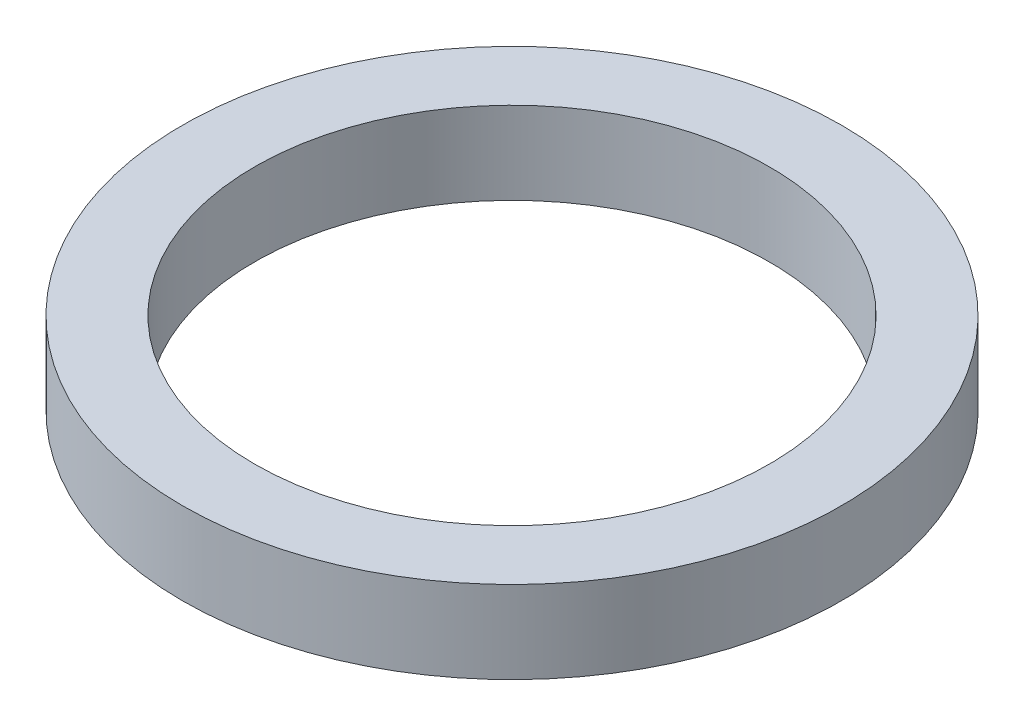
SolidWorks part; units mm, degrees
ref_plane "Front" through (0, 0, 0) normal (0, 0, 1) x (1, 0, 0)
ref_plane "Top" through (0, 0, 0) normal (0, 1, 0) x (1, 0, 0)
ref_plane "Right" through (0, 0, 0) normal (1, 0, 0) x (0, 0, -1)
sketch "Sketch1" plane through (0, 0, 0) normal (0, 1, 0) x (1, 0, 0)
  circle A0 centre (0, 0) radius 12.5
  circle A1 centre (0, 0) radius 16
  dimension "D1" = 32
  dimension "D2" = 25
extrude "Boss-Extrude1" add sketch "Sketch1" along normal blind 4
